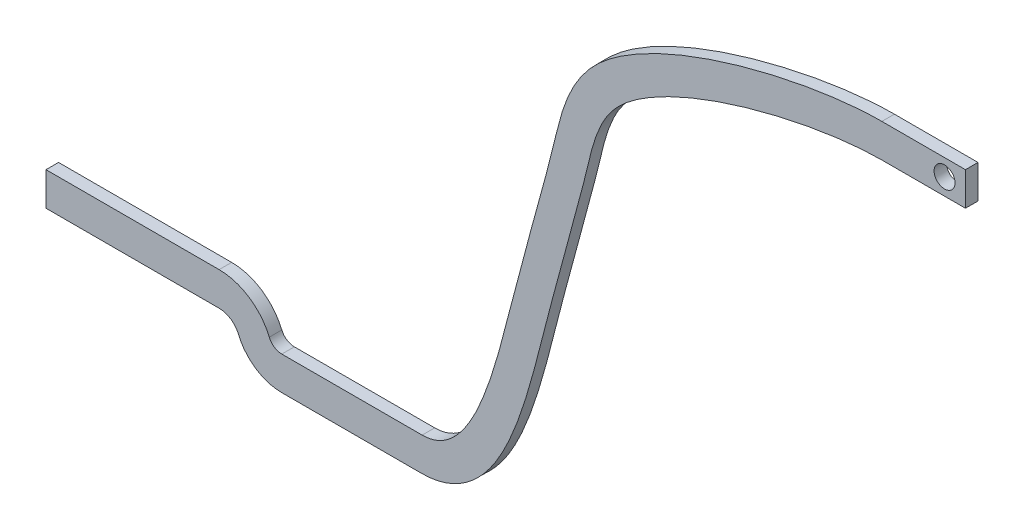
SolidWorks part; units mm, degrees
material "2014 Alloy"
ref_plane "Front Plane" through (0, 0, 0) normal (0, 0, 1) x (1, 0, 0)
ref_plane "Top Plane" through (0, 0, 0) normal (0, 1, 0) x (1, 0, 0)
ref_plane "Right Plane" through (0, 0, 0) normal (1, 0, 0) x (0, 0, -1)
sketch "Sketch1" plane through (0, 0, 0) normal (0, 0, 1) x (1, 0, 0)
  line L0 (0, 0) -> (41.4248, 0)
  line L1 (200, 110) -> (220, 110)
  line L2 (0, -8) -> (41.4248, -8)
  line L3 (200, 102) -> (220, 102)
  line L4 (0, 0) -> (0, -8)
  line L5 (220, 110) -> (220, 102)
  line L6 (3.4284, -12.7472) -> (89.7568, -18) construction
  line L7 (3.9142, -4.762) -> (90, -10) construction
  line L8 (56.4248, -10) -> (90, -10)
  line L9 (56.4248, -18) -> (89.7568, -18)
  arc A0 (41.4248, 0) -> (53.4248, -8) centre (41.4248, -13) cw
  arc A1 (41.4248, -8) -> (46.0401, -11.0769) centre (41.4248, -13) cw
  arc A2 (46.0401, -11.0769) -> (56.4248, -18) centre (56.4248, -6.75) ccw
  arc A3 (53.4248, -8) -> (56.4248, -10) centre (56.4248, -6.75) ccw
  spline S0 degree 3 poles (90, -10) (101.9432, -10) (114.6079, 42.0845) (120.2086, 59.1821) (128.3489, 97.0979) (181.2977, 110) (200, 110) knots 0 0 0 0 0.207627 0.498806 0.661293 1 1 1 1
  spline S1 degree 1 poles (89.7568, -18) (200, 102) knots 0 0 1 1 construction
  spline S2 degree 3 poles (89.7568, -18) (89.8131, -18) (89.9023, -17.9999) (90.0019, -18.0001) (90.2311, -17.9992) (90.473, -17.9945) (90.8841, -17.9802) (91.3881, -17.9491) (92.1948, -17.8716) (93.1905, -17.7229) (94.7507, -17.3782) (96.6187, -16.7577) (99.3771, -15.4234) (102.3432, -13.2591) (106.1749, -9.1893) (109.7351, -3.3867) (112.9617, 4.2464) (115.5143, 12.1792) (117.2517, 18.6296) (118.4741, 23.4122) (119.6025, 27.8231) (120.8985, 32.7926) (122.2842, 38.0013) (123.9432, 44.1257) (125.3696, 49.2901) (126.6664, 54.0397) (127.5976, 57.5239) (128.3582, 60.4703) (128.9663, 62.9054) (129.4293, 64.8061) (129.883, 66.7129) (130.4924, 69.171) (131.6706, 73.3007) (133.5431, 77.4976) (136.1709, 80.8434) (138.1179, 82.7221) (140.5061, 84.6809) (144.2081, 87.1527) (149.5906, 90.0086) (155.6798, 92.6583) (162.2576, 95.0444) (169.1118, 97.1263) (176.0352, 98.8731) (182.8213, 100.2596) (188.1872, 101.0966) (192.195, 101.5666) (195.0301, 101.818) (197.2172, 101.9427) (198.8579, 101.9919) (199.6139, 102) (200, 102) knots -0.001409 -0.001409 -0.001409 -0.001409 -0.000431 0.000058 0.000547 0.001525 0.002503 0.004459 0.006414 0.010326 0.014238 0.022061 0.029885 0.045532 0.061179 0.092473 0.123767 0.155061 0.186355 0.202002 0.217649 0.248943 0.280237 0.311531 0.374119 0.405413 0.436707 0.468001 0.483648 0.499295 0.514942 0.530589 0.561884 0.624472 0.655766 0.671413 0.68706 0.718354 0.749648 0.780942 0.812236 0.84353 0.874824 0.906118 0.937412 0.953059 0.968706 0.984353 0.992176 1 1 1 1
  dimension "D2" = 120
  dimension "D3" = 8
  dimension "D4" = 130
  dimension "D1" = 5
  dimension "D6" = 8
  dimension "D8" = 220
  dimension "D5" = 20
  dimension "D7" = 10
extrude "Boss-Extrude1" add sketch "Sketch1" along normal blind 3 contours L0 A0 A3 L8 S0 L1 L5 L3 S2 L9 A2 A1 L2 L4
sketch "Sketch2" plane through (0, 0, 3) normal (0, 0, 1) x (1, 0, 0)
  line L0 (200, 110) -> (220, 110) construction
  line L1 (220, 110) -> (220, 102) construction
  circle A0 centre (215, 106) radius 2.5
  point P8 (220, 106)
  dimension "D3" = 5
  dimension "D1" = 4
  dimension "D2" = 5
extrude "Cut-Extrude1" cut sketch "Sketch2" against normal up to surface (3 mm away) up to face at (86.0804, 15.2437, 0)
